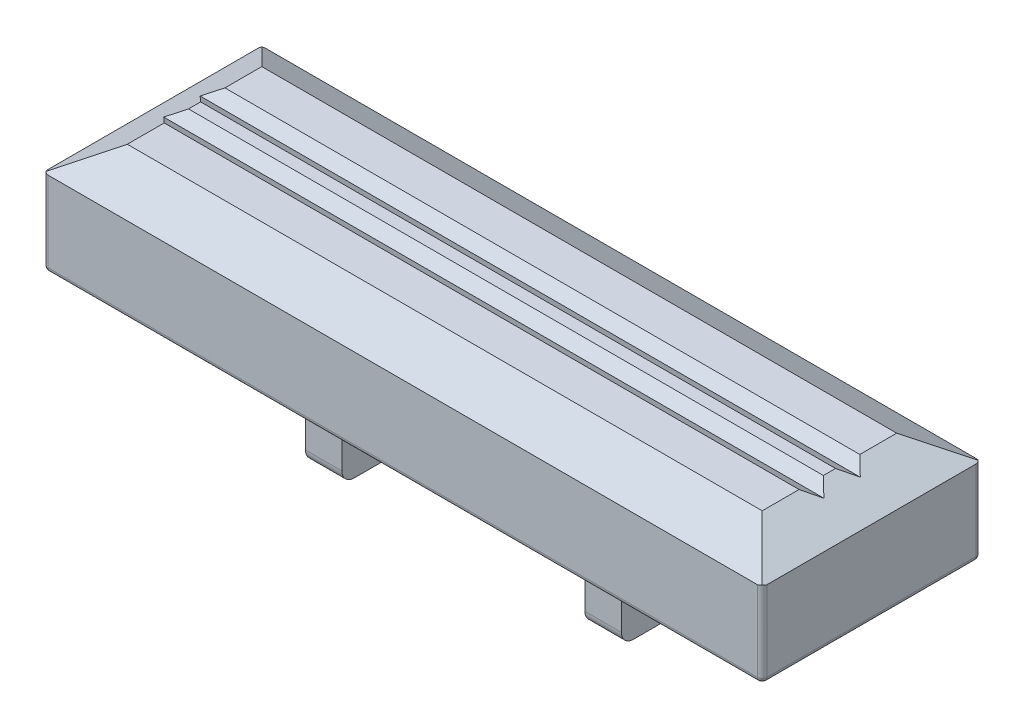
SolidWorks part; units mm, degrees
ref_plane "前视基准面" through (0, 0, 0) normal (0, 0, 1) x (1, 0, 0)
ref_plane "上视基准面" through (0, 0, 0) normal (0, 1, 0) x (1, 0, 0)
ref_plane "右视基准面" through (0, 0, 0) normal (1, 0, 0) x (0, 0, -1)
sketch "草图1" plane through (0, 0, 0) normal (0, 1, 0) x (1, 0, 0)
  line L1 (-14.8, -4.5) -> (14.8, -4.5)
  line L2 (-14.8, -4.5) -> (-14.8, 4.5)
  line L3 (-14.8, 4.5) -> (14.8, 4.5)
  line L4 (14.8, -4.5) -> (14.8, 4.5)
extrude "凸台-拉伸1" add sketch "草图1" along normal blind 4.5
sketch "草图2" plane through (0, 0, 0) normal (0, -1, 0) x (1, 0, 0)
  line L0 (-13.3, 0.5) -> (-13.3, 3)
  line L1 (-13.3, -3) -> (13.3, -3)
  line L2 (-13.3, -3) -> (-13.3, -0.5)
  line L3 (-13.3, 3) -> (13.3, 3)
  line L4 (13.3, -3) -> (13.3, -0.5)
  line L5 (-13.3, -0.5) -> (-6.5, -0.5)
  line L6 (13.3, 0.5) -> (13.3, 3)
  line L7 (-13.3, 0.5) -> (-6.5, 0.5)
  line L8 (-6.5, -0.5) -> (-6.5, 0.5)
  line L9 (6.5, -0.5) -> (13.3, -0.5)
  line L10 (6.5, -0.5) -> (6.5, 0.5)
  line L11 (6.5, 0.5) -> (13.3, 0.5)
extrude "切除-拉伸1" cut sketch "草图2" against normal blind 3
sketch "草图3" plane through (0, 3, 0) normal (0, -1, 0) x (1, 0, 0)
  line L1 (-6.5, -2) -> (-5, -2)
  line L2 (-6.5, -2) -> (-6.5, 2)
  line L3 (-6.5, 2) -> (-5, 2)
  line L4 (-5, -2) -> (-5, 2)
  line L5 (5, -2) -> (6.5, -2)
  line L6 (5, -2) -> (5, 2)
  line L7 (5, 2) -> (6.5, 2)
  line L8 (6.5, -2) -> (6.5, 2)
extrude "凸台-拉伸2" add sketch "草图3" along normal blind 7
sketch "草图4" plane through (-6.5, 0, 0) normal (-1, 0, 0) x (0, 0, 1)
  line L1 (-1, -3) -> (1, -3)
  line L2 (-1, -3) -> (-1, -1)
  line L3 (-1, -1) -> (1, -1)
  line L4 (1, -3) -> (1, -1)
extrude "切除-拉伸2" cut sketch "草图4" against normal through all
chamfer "倒角1" distance 1 angle 60 2 edges at (0, 4.5, -4.5) (0, 4.5, 4.5)
chamfer "倒角2" distance 1 angle 60 2 edges at (-14.8, 4.5, 0) (14.8, 4.5, 0)
sketch "草图5" plane through (-14.8, 0, 0) normal (-1, 0, 0) x (0, 0, 1)
  line L0 (-1.25, 4.5) -> (-0.25, 4.5)
  line L2 (0.75, 4.2) -> (1.25, 4.5)
  line L3 (0.75, 4.2) -> (0.25, 4.5)
  line L4 (1.25, 4.5) -> (0.25, 4.5)
  line L8 (-0.75, 4.2) -> (-0.25, 4.5)
  line L9 (-0.75, 4.2) -> (-1.25, 4.5)
extrude "切除-拉伸3" cut sketch "草图5" against normal through all
fillet "圆角2" radius 0.2 8 edges at (-14.8, 1.75, 4.5) (-14.8, 0, 0) (0, 0, -4.5) (-14.8, 1.75, -4.5) (14.8, 1.75, -4.5) (14.8, 0, 0) (0, 0, 4.5) (14.8, 1.75, 4.5)
fillet "圆角3" radius 0.5 4 edges at (-5.75, -4, 2) (-5.75, -4, -2) (5.75, -4, 2) (5.75, -4, -2)
